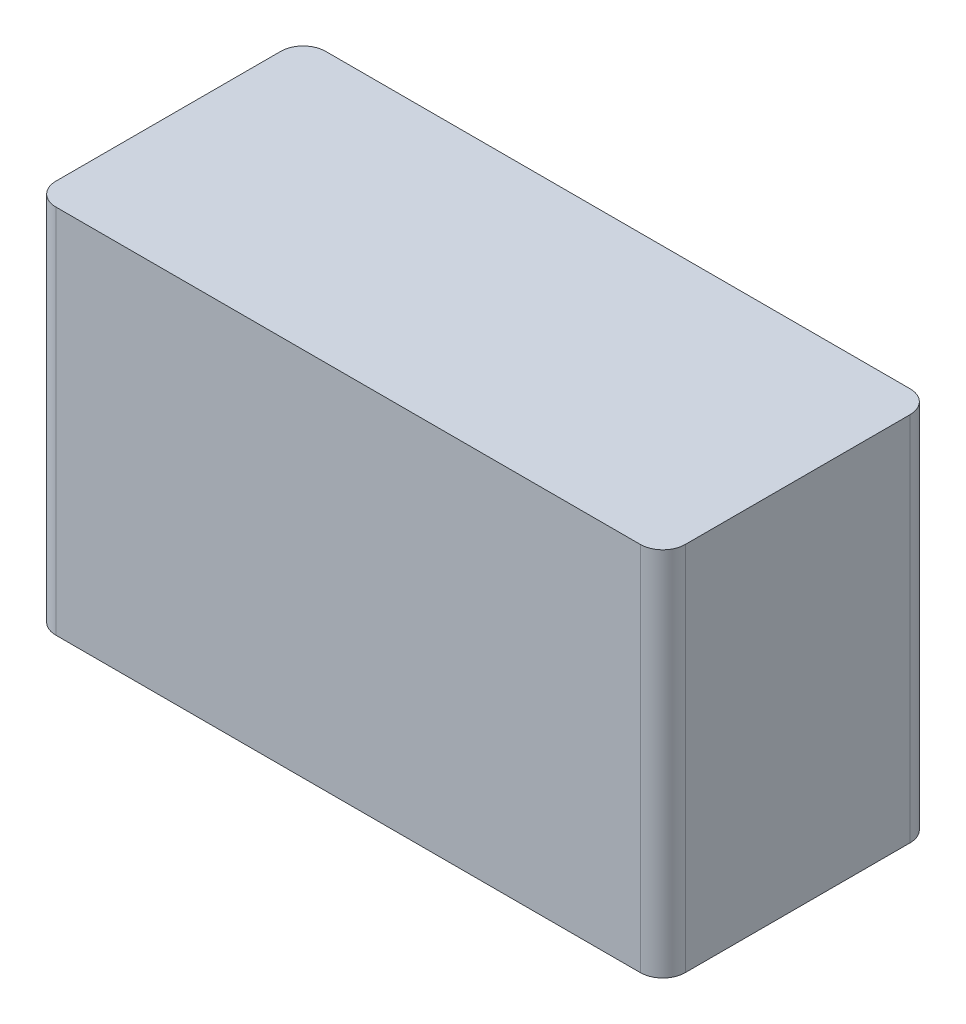
SolidWorks part; units mm, degrees
material "Pine"
ref_plane "Front Plane" through (0, 0, 0) normal (0, 0, 1) x (1, 0, 0)
ref_plane "Top Plane" through (0, 0, 0) normal (0, 1, 0) x (1, 0, 0)
ref_plane "Right Plane" through (0, 0, 0) normal (1, 0, 0) x (0, 0, -1)
sketch "Sketch2" plane through (0, 0, 0) normal (0, 1, 0) x (1, 0, 0)
  line L1 (0, 0) -> (88.9, 0)
  line L2 (0, 0) -> (0, 38.1)
  line L3 (0, 38.1) -> (88.9, 38.1)
  line L4 (88.9, 0) -> (88.9, 38.1)
  dimension "D1" = 88.9
  dimension "D2" = 38.1
extrude "Boss-Extrude1" add sketch "Sketch2" along normal blind 52.3875
fillet "Fillet1" radius 3.175 4 edges at (0, 26.1937, -38.1) (88.9, 26.1937, -38.1) (0, 26.1937, 0) (88.9, 26.1937, 0)
equation "\"D1@Boss-Extrude1\"=3-2*.46875"
